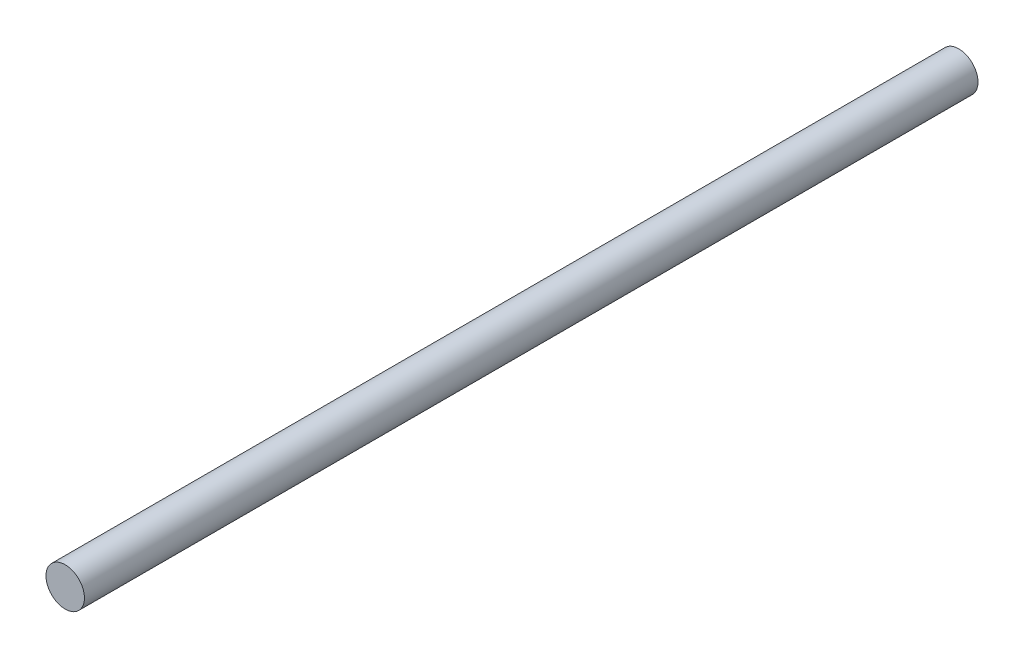
SolidWorks part; units mm, degrees
material "PVC Rigid"
ref_plane "Front Plane" through (0, 0, 0) normal (0, 0, 1) x (1, 0, 0)
ref_plane "Top Plane" through (0, 0, 0) normal (0, 1, 0) x (1, 0, 0)
ref_plane "Right Plane" through (0, 0, 0) normal (1, 0, 0) x (0, 0, -1)
ref_plane "Plane1" through (0, 0, 70) normal (0, 0, 1) x (1, 0, 0)
sketch "Sketch2" plane through (0, 0, 70) normal (0, 0, 1) x (1, 0, 0)
  circle A0 centre (0, 0) radius 53
  circle A1 centre (0, 0) radius 55
extrude "Boss-Extrude1" add sketch "Sketch2" along normal blind 2500
ref_plane "Plane2" through (0, 0, 2570) normal (0, 0, 1) x (1, 0, 0)
sketch "Sketch3" plane through (0, 0, 2570) normal (0, 0, 1) x (1, 0, 0)
  circle A0 centre (0, 0) radius 55
extrude "Boss-Extrude2" add sketch "Sketch3" along normal blind 55
